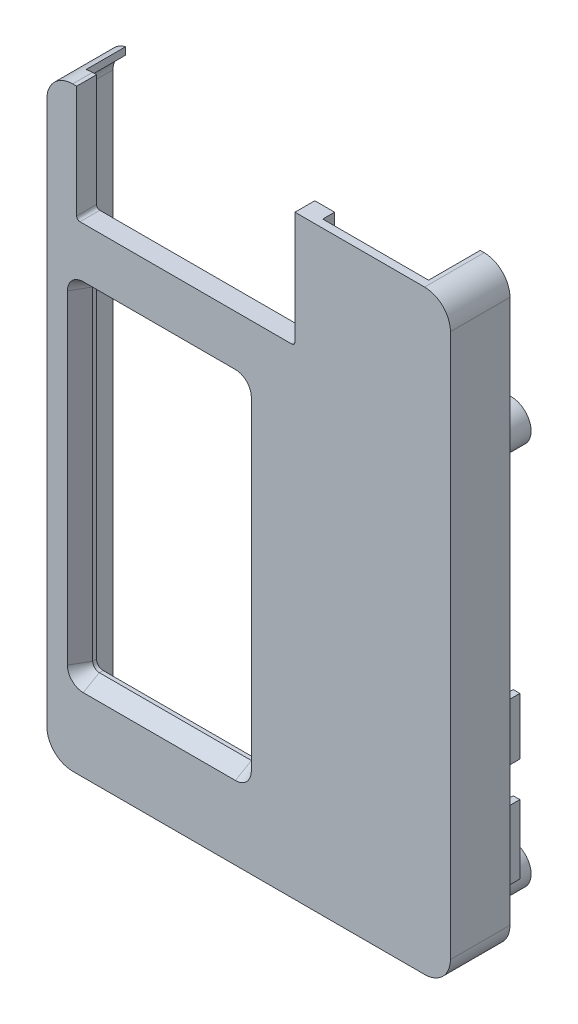
SolidWorks part; units mm, degrees
ref_plane "前视基准面" through (0, 0, 0) normal (0, 0, 1) x (1, 0, 0)
ref_plane "上视基准面" through (0, 0, 0) normal (0, 1, 0) x (1, 0, 0)
ref_plane "右视基准面" through (0, 0, 0) normal (1, 0, 0) x (0, 0, -1)
other "Configuration Table"
sketch "草图1" plane through (0, 0, 0) normal (0, 0, 1) x (1, 0, 0)
  line L1 (-30.5, -45) -> (30.5, -45)
  line L2 (-30.5, -45) -> (-30.5, 45)
  line L3 (-30.5, 45) -> (30.5, 45)
  line L4 (30.5, -45) -> (30.5, 45)
  line L5 (-30.5, -45) -> (30.5, 45) construction
  line L6 (-30.5, 45) -> (30.5, -45) construction
  point P0 (0, 0)
extrude "凸台-拉伸1" add sketch "草图1" along normal blind 3
sketch "草图2" plane through (0, 0, 3) normal (0, 0, 1) x (1, 0, 0)
  line L1 (-26, 42.5) -> (26, 42.5)
  line L2 (-28, 40.5) -> (-28, -40.5)
  line L3 (-26, -42.5) -> (26, -42.5)
  line L4 (28, 40.5) -> (28, -40.5)
  line L5 (-28, 42.5) -> (28, -42.5) construction
  line L6 (-28, -42.5) -> (28, 42.5) construction
  arc A0 (-28, 40.5) -> (-26, 42.5) centre (-26, 40.5) cw
  arc A1 (28, 40.5) -> (26, 42.5) centre (26, 40.5) ccw
  arc A2 (26, -42.5) -> (28, -40.5) centre (26, -40.5) ccw
  arc A3 (-26, -42.5) -> (-28, -40.5) centre (-26, -40.5) cw
  point P0 (0, 0)
  dimension "D1" = 2
sketch "草图3" plane through (0, 0, 3) normal (0, 0, 1) x (1, 0, 0)
  line L0 (-26, -42.5) -> (26, -42.5) construction
  line L1 (-26, -32.5) -> (-1, -32.5)
  line L2 (-26, -32.5) -> (-26, 18.5)
  line L3 (-26, 18.5) -> (-1, 18.5)
  line L4 (-1, -32.5) -> (-1, 18.5)
  line L5 (-26, -32.5) -> (-1, 18.5) construction
  line L6 (-26, 18.5) -> (-1, -32.5) construction
  line L7 (-28, 40.5) -> (-28, -40.5) construction
  point P4 (-13.5, -7)
  dimension "D1" = 10
  dimension "D2" = 2
  dimension "D3" = 51
  dimension "D4" = 25
extrude "切除-拉伸1" cut sketch "草图3" against normal up to surface (3 mm away) up to face at (0, 0, 0)
fillet "圆角1" radius 1 4 edges at (-1, 18.5, 1.5) (-1, -32.5, 1.5) (-26, -32.5, 1.5) (-26, 18.5, 1.5)
chamfer "倒角1" distance 1.4 angle 60 8 edges at (-1, -7, 3) (-1.2929, 18.2071, 3) (-1.2929, -32.2071, 3) (-13.5, 18.5, 3) (-13.5, -32.5, 3) (-25.7071, 18.2071, 3) (-25.7071, -32.2071, 3) (-26, -7, 3)
sketch "草图4" plane through (0, 0, 3) normal (0, 0, 1) x (1, 0, 0)
  circle A0 centre (24.5, 19) radius 3
  circle A1 centre (24.5, -39) radius 3
sketch "草图7" plane through (0, 0, 0) normal (0, 0, -1) x (-1, 0, 0)
  circle A1 centre (-24.5, -39) radius 3
  circle A2 centre (-24.5, -39) radius 3
  circle A3 centre (-24.5, 19) radius 3
  circle A4 centre (-24.5, 19) radius 3
  dimension "D1" = 0
  dimension "D2" = 0
extrude "凸台-拉伸2" add sketch "草图7" along normal blind 12.2
chamfer "倒角2" distance 1 angle 70 2 edges at (21.5, -39, 0) (21.5, 19, 0)
sketch "草图8" plane through (0, 0, -12.2) normal (0, 0, -1) x (-1, 0, 0)
  circle A0 centre (-24.5, 19) radius 1.3
  circle A1 centre (-24.5, -39) radius 1.3
extrude "切除-拉伸2" cut sketch "草图8" against normal blind 6
chamfer "倒角3" distance 0.4 angle 70 2 edges at (23.2, -39, -12.2) (23.2, 19, -12.2)
sketch "草图9" plane through (0, 0, 3) normal (0, 0, 1) x (1, 0, 0)
  line L4 (28.5, 1.3) -> (29.5, 1.3)
  line L5 (28.5, 1.3) -> (28.5, -7.3)
  line L10 (28.5, -7.3) -> (29.5, -7.3)
  line L11 (29.5, 1.3) -> (29.5, -7.3)
  line L16 (28.5, 1.3) -> (29.5, -7.3) construction
  line L17 (28.5, -7.3) -> (29.5, 1.3) construction
  line L18 (28.5, -12.5) -> (29.5, -12.5)
  line L19 (28.5, -12.5) -> (28.5, -21.1)
  line L20 (28.5, -21.1) -> (29.5, -21.1)
  line L21 (29.5, -12.5) -> (29.5, -21.1)
  line L22 (28.5, -12.5) -> (29.5, -21.1) construction
  line L23 (28.5, -21.1) -> (29.5, -12.5) construction
  line L24 (28.5, -26.4) -> (29.5, -26.4)
  line L25 (28.5, -26.4) -> (28.5, -36.8)
  line L26 (28.5, -36.8) -> (29.5, -36.8)
  line L27 (29.5, -26.4) -> (29.5, -36.8)
  line L28 (28.5, -26.4) -> (29.5, -36.8) construction
  line L29 (28.5, -36.8) -> (29.5, -26.4) construction
  point P4 (29, -3)
  point P9 (29, -16.8)
  point P14 (29, -31.6)
  point P15 (0, 0)
  dimension "D1" = 1
  dimension "D2" = 1
  dimension "D3" = 1
  dimension "D4" = 8.6
  dimension "D5" = 8.6
  dimension "D6" = 10.4
sketch "草图10" plane through (0, 0, 0) normal (0, 0, -1) x (-1, 0, 0)
  line L28 (-28.5, -26.4) -> (-29.5, -26.4)
  line L29 (-29.5, -26.4) -> (-29.5, -36.8)
  line L30 (-29.5, -36.8) -> (-28.5, -36.8)
  line L31 (-28.5, -36.8) -> (-28.5, -26.4)
  line L32 (-28.5, -26.4) -> (-29.5, -26.4)
  line L33 (-29.5, -26.4) -> (-29.5, -36.8)
  line L34 (-29.5, -36.8) -> (-28.5, -36.8)
  line L35 (-28.5, -36.8) -> (-28.5, -26.4)
  line L36 (-28.5, -12.5) -> (-29.5, -12.5)
  line L37 (-29.5, -12.5) -> (-29.5, -21.1)
  line L38 (-29.5, -21.1) -> (-28.5, -21.1)
  line L39 (-28.5, -21.1) -> (-28.5, -12.5)
  line L40 (-28.5, -12.5) -> (-29.5, -12.5)
  line L41 (-29.5, -12.5) -> (-29.5, -21.1)
  line L42 (-29.5, -21.1) -> (-28.5, -21.1)
  line L43 (-28.5, -21.1) -> (-28.5, -12.5)
  line L44 (-28.5, 1.3) -> (-29.5, 1.3)
  line L45 (-29.5, 1.3) -> (-29.5, -7.3)
  line L46 (-29.5, -7.3) -> (-28.5, -7.3)
  line L47 (-28.5, -7.3) -> (-28.5, 1.3)
  line L48 (-28.5, 1.3) -> (-29.5, 1.3)
  line L49 (-29.5, 1.3) -> (-29.5, -7.3)
  line L50 (-29.5, -7.3) -> (-28.5, -7.3)
  line L51 (-28.5, -7.3) -> (-28.5, 1.3)
  dimension "D1" = 0
  dimension "D2" = 0
  dimension "D3" = 0
extrude "凸台-拉伸3" add sketch "草图10" along normal blind 8.5
sketch "草图11" plane through (0, 0, 0) normal (0, 0, -1) x (-1, 0, 0)
  line L0 (-29.5, 44) -> (-29.5, -44)
  line L1 (-29.5, -44) -> (29.5, -44)
  line L2 (29.5, -44) -> (29.5, 44)
  line L3 (29.5, 44) -> (-29.5, 44)
  line L4 (-30.5, 45) -> (-30.5, -45)
  line L5 (-30.5, -45) -> (30.5, -45)
  line L6 (30.5, -45) -> (30.5, 45)
  line L7 (30.5, 45) -> (-30.5, 45)
  line L8 (-30.5, 45) -> (-30.5, -45)
  line L9 (-30.5, -45) -> (30.5, -45)
  line L10 (30.5, -45) -> (30.5, 45)
  line L11 (30.5, 45) -> (-30.5, 45)
  dimension "D1" = 0
  dimension "D2" = 1
extrude "凸台-拉伸4" add sketch "草图11" along normal blind 6
fillet "圆角2" radius 3.1 4 edges at (29.5, 44, -3) (-29.5, 44, -3) (-29.5, -44, -3) (29.5, -44, -3)
fillet "圆角3" radius 3.9 4 edges at (30.5, 45, -1.5) (-30.5, 45, -1.5) (-30.5, -45, -1.5) (30.5, -45, -1.5)
sketch "草图12" plane through (0, 0, -6) normal (0, 0, -1) x (-1, 0, 0)
  line L0 (26.6, 45) -> (-26.6, 45) construction
  line L1 (-26, 45) -> (27.6, 45)
  line L2 (-26, 45) -> (-26, 44)
  line L3 (-26, 44) -> (26.4, 44)
  line L4 (27.6, 45) -> (27.6, 43.7583)
  line L5 (-26, 45) -> (0.8, 44.5) construction
  line L6 (-26, 44) -> (27.6, 45) construction
  arc A0 (29.5, 40.9) -> (26.4, 44) centre (26.4, 40.9) ccw construction
  arc A1 (27.6, 43.7583) -> (26.4, 44) centre (26.4, 40.9) ccw
  point P4 (0.8, 44.5)
extrude "切除-拉伸3" cut sketch "草图12" against normal up to surface (6 mm away) up to face at (17.4, -10.28, 0)
sketch "草图13" plane through (0, 0, 3) normal (0, 0, 1) x (1, 0, 0)
  line L0 (26.6, 45) -> (-26.6, 45) construction
  line L1 (-26, 45) -> (7, 45)
  line L2 (-26, 45) -> (-26, 27.5)
  line L3 (-26, 27.5) -> (7, 27.5)
  line L4 (7, 45) -> (7, 27.5)
  line L5 (-26, 45) -> (7, 27.5) construction
  line L6 (-26, 27.5) -> (7, 45) construction
  line L7 (-28, 40.5) -> (-28, -40.5) construction
  line L8 (-26, 42.5) -> (26, 42.5) construction
  point P4 (-9.5, 36.25)
  dimension "D1" = 2
  dimension "D2" = 15
  dimension "D3" = 33
extrude "切除-拉伸4" cut sketch "草图13" against normal up to surface (3 mm away) up to face at (14.3669, -1.1373, 0)
fillet "圆角4" radius 0.5 2 edges at (7, 27.5, 1.5) (-26, 27.5, 1.5)
sketch "草图14" plane through (0, 0, 0) normal (0, 0, -1) x (-1, 0, 0)
  line L0 (-26, 45) -> (-7, 45) construction
  line L1 (-26, 45) -> (-10, 45)
  line L2 (-26, 45) -> (-26, 23.5)
  line L3 (-26, 23.5) -> (-10, 23.5)
  line L4 (-10, 45) -> (-10, 23.5)
  line L5 (-26, 45) -> (-10, 23.5) construction
  line L6 (-26, 23.5) -> (-10, 45) construction
  line L7 (-28, 40.5) -> (-28, -40.5) construction
  line L8 (26, 42.5) -> (-26, 42.5) construction
  point P4 (-18, 34.25)
  dimension "D1" = 2
  dimension "D2" = 16
  dimension "D3" = 19
extrude "切除-拉伸5" cut sketch "草图14" against normal blind 1.8
sketch "草图15" plane through (29.5, 0, 0) normal (1, 0, 0) x (0, 0, -1)
  line L12 (8.5, 1.3) -> (6, 1.3)
  line L13 (6, 1.3) -> (6, -7.3)
  line L14 (6, -7.3) -> (8.5, -7.3)
  line L15 (8.5, -7.3) -> (8.5, 1.3)
  line L16 (8.5, 1.3) -> (6, 1.3)
  line L17 (6, 1.3) -> (6, -7.3)
  line L18 (6, -7.3) -> (8.5, -7.3)
  line L19 (8.5, -7.3) -> (8.5, 1.3)
  dimension "D1" = 0
extrude "切除-拉伸6" cut sketch "草图15" against normal up to surface (1 mm away) up to face at (28.5, -16.8, -4.25)
